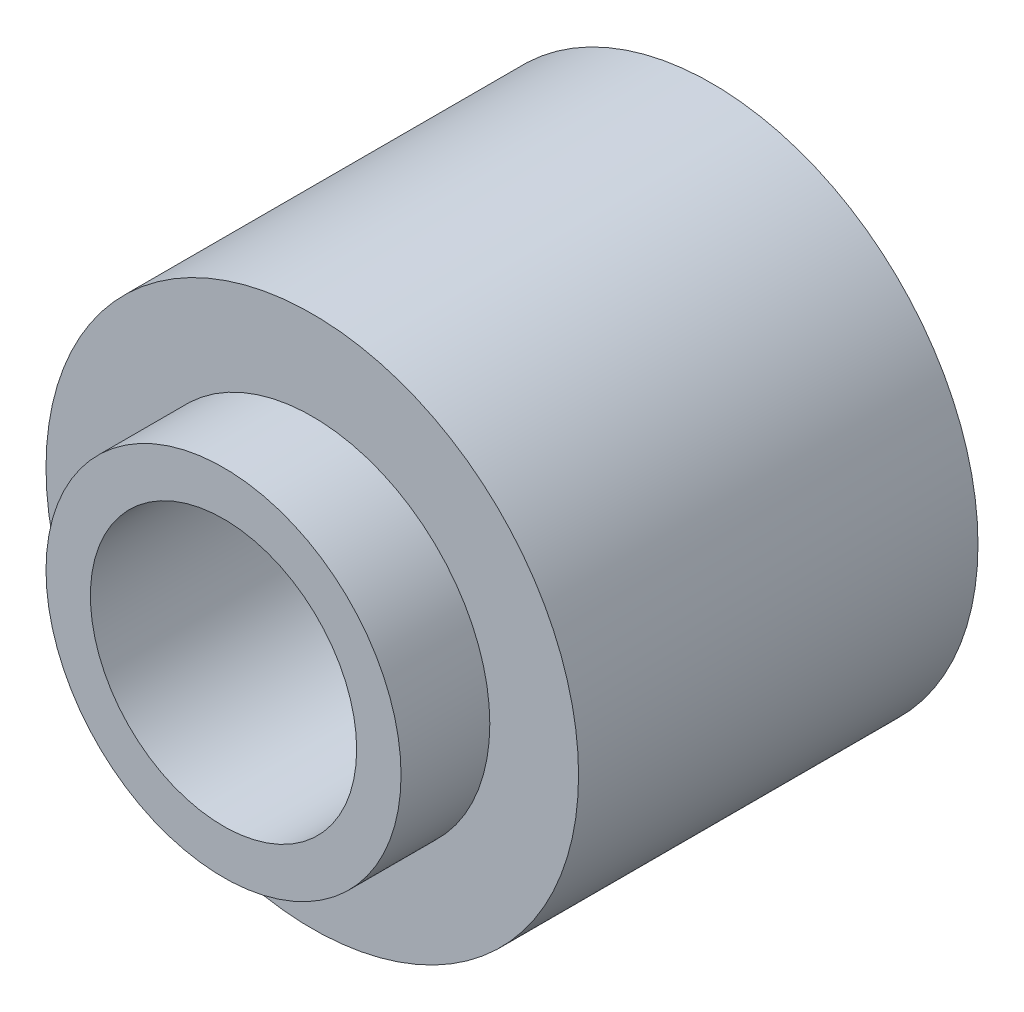
SolidWorks part; units mm, degrees
ref_plane "前视基准面" through (0, 0, 0) normal (0, 0, 1) x (1, 0, 0)
ref_plane "上视基准面" through (0, 0, 0) normal (0, 1, 0) x (1, 0, 0)
ref_plane "右视基准面" through (0, 0, 0) normal (1, 0, 0) x (0, 0, -1)
other "Configuration Table"
sketch "草图1" plane through (0, 0, 0) normal (0, 0, 1) x (1, 0, 0)
  circle A0 centre (0, 0) radius 6
  circle A1 centre (0, 0) radius 3
  dimension "D1" = 12
  dimension "D2" = 6
extrude "凸台-拉伸1" add sketch "草图1" along normal blind 9 contours A0 A1
sketch "草图2" plane through (0, 0, 9) normal (0, 0, 1) x (1, 0, 0)
  circle A1 centre (0, 0) radius 3
  circle A2 centre (0, 0) radius 4
  dimension "D1" = 6
  dimension "D2" = 8
extrude "凸台-拉伸2" add sketch "草图2" along normal blind 2
